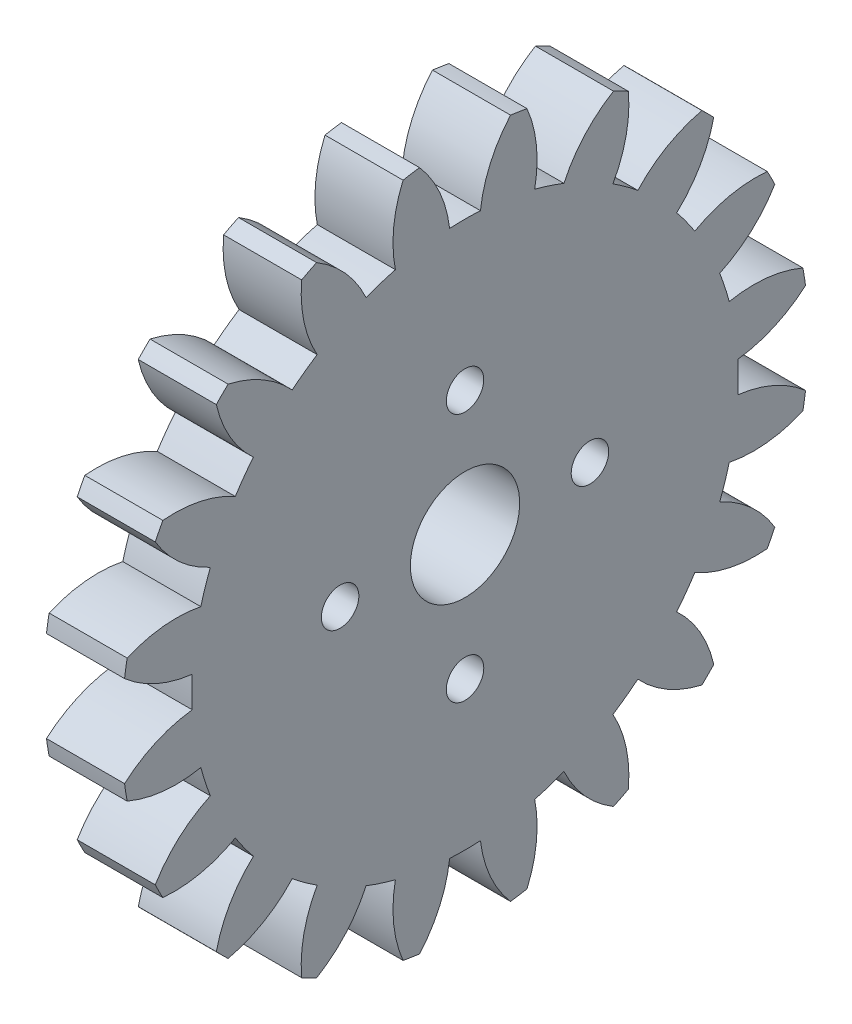
SolidWorks part; units mm, degrees
ref_plane "Plane1" through (0, 0, 0) normal (0, 0, 1) x (1, 0, 0)
ref_plane "Plane2" through (0, 0, 0) normal (0, 1, 0) x (1, 0, 0)
ref_plane "Plane3" through (0, 0, 0) normal (1, 0, 0) x (0, 0, -1)
sketch "HoldingSke" plane through (0, 0, 0) normal (0, 1, 0) x (1, 0, 0)
  line L0 (0, 0) -> (0.4698, -0.171)
  line L1 (-15, 0) -> (100, 0) construction
  line L2 (0, 0) -> (-2.1039, 2.3779)
  line L3 (0, 0) -> (-11.863, 4.5341)
  line L4 (0, 0) -> (8.1152, 2.9537)
  line L5 (0, 0) -> (-46.8476, -17.4728)
  line L6 (0, 0) -> (-4.1448, -2.7965)
  line L7 (-2.1039, 2.3779) -> (8.6586, 51.2059)
  line L8 (-76.2, 54.61) -> (-75.2, 54.61)
  line L9 (-71.009, 38.7566) -> (-53.1078, 45.2721)
  line L10 (-76.2, 71.12) -> (104.1128, 71.12)
  line L11 (0, 0) -> (-5, 0)
  line L12 (-76.2, 101.6) -> (-76.133, 101.6)
  line L13 (24.9733, 27.94) -> (52.9518, 28.4284)
  line L14 (24.9733, 27.94) -> (24.9743, 27.94)
  line L15 (24.9733, 27.94) -> (100.4006, 29.5858)
  line L16 (-63.627, -2) -> (-12.827, -2)
  circle A0 centre (0, 0) radius 3.5
  circle A1 centre (0, 0) radius 17.499
  circle A2 centre (0, 0) radius 37.5
  circle A3 centre (0, 0) radius 3.5
  dimension "MHD" = 34.998
  dimension "Hub_dia" = 75
  dimension "Bore" = 7
  dimension "MBD" = 7
  dimension "Num_teeth" = 20
  dimension "Pitch" = 0.5
  dimension "Overall_len" = 50
  dimension "Show_teeth" = 20
  dimension "Thickness" = 5
  dimension "OAL" = 50.0001
  dimension "T_dim" = 1
  dimension "Ap" = 20
  dimension "H" = 19.05
  dimension "Pitch_radius" = 180.3128
  dimension "Width" = 5
  dimension "Backlash" = 0.067
  dimension "Addendum_fac" = 1
  dimension "Dedendum_fac" = 1.25
  dimension "Clearance_fac" = 0.25
  dimension "Dedendum_add" = 0.001
  dimension "Module" = 2
sketch "BasProSke" plane through (0, 0, 0) normal (0, 1, 0) x (1, 0, 0)
  line L0 (-10, 0) -> (60, 0) construction
  line L1 (0, 0) -> (0, 22)
  line L2 (0, 0) -> (5, 0)
  line L3 (5, 0) -> (5, 22)
  line L4 (5, 22) -> (0, 22)
  dimension "Thickness" = 5
  dimension "Diameter" = 44
revolve "Base-Revolve" add sketch "BasProSke" angle 360 about L0
sketch "TooCutSke" plane through (0, 0, 0) normal (1, 0, 0) x (0, 0, -1)
  line L1 (0, 0) -> (0, 107) construction
  line L2 (0, 0) -> (-1.6864, 19.9288) construction
  line L3 (0, 0) -> (-6.2409, 39.4033) construction
  line L4 (-1.6864, 19.9288) -> (-3.1204, 19.7016) construction
  arc A0 (0.9862, 17.4712) -> (-0.9862, 17.4712) centre (0, 0) ccw
  arc A1 (2.9329, 21.8293) -> (-2.9329, 21.8293) centre (0, 0) ccw
  circle A2 centre (0, 0) radius 20 construction
  circle A3 centre (0, 0) radius 18.7939 construction
  arc A4 (-0.9862, 17.4712) -> (-2.9329, 21.8293) centre (-8.9313, 16.536) ccw
  arc A5 (2.9329, 21.8293) -> (0.9862, 17.4712) centre (8.9313, 16.536) ccw
  dimension "Root_dia" = 34.998
  dimension "Overcut_dia" = 44.0508
  dimension "Pitch_dia" = 40
  dimension "Base_dia" = 37.5877
  dimension "Flank_rad" = 8
  dimension "Half_ang" = 9
  dimension "Half_CT" = 1.4519
extrude "ToothCut" cut sketch "TooCutSke" along normal through all
fillet "Breaks" [suppressed] radius 0.04
fillet "RootFillets" [suppressed] radius 0.501
pattern_circular "TeethCuts" count 20 every 18 about axis through (-10, 0, 0) along (1, 0, 0) of "ToothCut", "RootFillets", "Breaks"
sketch "HubNeaOneSke" plane through (0, 0, 0) normal (-1, 0, 0) x (0, 0, 1)
  circle A0 centre (0, 0) radius 17.499
  dimension "Diameter" = 34.998
extrude "HubNearOne" [suppressed] add sketch "HubNeaOneSke" along normal blind 45.0001
sketch "HubNeaBotSke" plane through (0, 0, 0) normal (-1, 0, 0) x (0, 0, 1)
  circle A0 centre (0, 0) radius 17.499
  dimension "Diameter" = 34.998
extrude "HubNearBoth" [suppressed] add sketch "HubNeaBotSke" along normal blind 22.5
ref_plane "FarPln" through (5, 0, 0) normal (1, 0, 0) x (0, 0, -1)
sketch "HubFarSke" plane through (5, 0, 0) normal (1, 0, 0) x (0, 0, -1)
  circle A0 centre (0, 0) radius 17.499
  dimension "Diameter" = 34.998
extrude "HubFar" [suppressed] add sketch "HubFarSke" along normal blind 22.5
sketch "BorSke" plane through (0, 0, 0) normal (1, 0, 0) x (0, 0, -1)
  circle A0 centre (0, 0) radius 3.5
  dimension "Diameter" = 7
extrude "Bore" cut sketch "BorSke" along normal mid plane 100.0001
sketch "KeySke" plane through (0, 0, 0) normal (1, 0, 0) x (0, 0, -1)
  line L0 (-1, 0) -> (-1, 4.5)
  line L1 (-1, 4.5) -> (1, 4.5)
  line L2 (1, 4.5) -> (1, 0)
  line L3 (0, 0) -> (0, 34) construction
  line L4 (-1, 0) -> (1, 0)
  dimension "Offset" = 4.5
  dimension "Width" = 2
extrude "Keyway" [suppressed] cut sketch "KeySke" along normal mid plane 100.0001
pattern_circular "Keyway2" [suppressed] count 2 every 90 about axis through (-10, 0, 0) along (1, 0, 0)
sketch "Esquisse1" plane through (0, 0, 0) normal (-1, 0, 0) x (0, 0, 1)
  circle A0 centre (0, 0) radius 8 construction
  circle A1 centre (0, 8) radius 0.5
  point P5 (0, 0)
  dimension "D1" = 16
  dimension "D2" = 1
hole_wizard "Fraisage pour vis à tête fraisée M21" positions "Esquisse2" profile "Esquisse3" countersink size "M2" standard "ISO" end condition up to next
sketch "Esquisse2" plane through (0, 0, 0) normal (-1, 0, 0) x (0, 0, 1)
  point P0 (0, 8)
sketch "Esquisse3" plane through (0, 8, 0) normal (0, 1, 0) x (0, 0, 1)
  line L0 (0, 0) -> (0, 5)
  line L1 (0, 5) -> (1.2, 5)
  line L2 (1.2, 5) -> (1.2, 1)
  line L3 (1.2, 1) -> (2.2, 0)
  line L5 (2.2, 0) -> (0, 0)
  line L6 (-1.2, 1) -> (-2.2, 0) construction
  line L11 (0, -6.35) -> (0, 107.95) construction
  dimension "Diamètre du perçage jusqu'au prochain" = 2.4
  dimension "Profondeur du perçage jusqu'au prochain" = 5
  dimension "Diamètre du fraisage entrant" = 4.4
  dimension "Angle du fraisage entrant" = 90
pattern_circular "Répétition circulaire1" count 4 over 360 about axis through (0, 0, 0) along (1, 0, 0) of "Fraisage pour vis à tête fraisée M21"
equation "' \"Module@HoldingSke\" = 6.35"
equation "' \"Num_teeth@HoldingSke\" = 12"
equation "' \"Ap@HoldingSke\" =  20"
equation "' \"Ap@HoldingSke\" = 20"
equation "' \"Width@HoldingSke\" = 0.5 * 25.4"
equation "' \"Hub_dia@HoldingSke\"= 1 * 25.4"
equation "' \"Hub_dia@HoldingSke\" = 1 * 25.4"
equation "' \"Overall_len@HoldingSke\" = 1.0 * 25.4"
equation "' \"Bore@HoldingSke\" = 0.75 * 25.4"
equation "' \"T_dim@HoldingSke\" = 0.1 * 25.4"
equation "' \"Width@KeySke\" = 0.25 * 25.4"
equation "' \"Show_teeth@HoldingSke\" = 13"
equation "' \"Backlash@HoldingSke\" = 0.009 * 25.4"
equation "' \"Addendum_fac@HoldingSke\" = 1.0"
equation "' \"Dedendum_fac@HoldingSke\" = 1.25"
equation "' \"Dedendum_add@HoldingSke\" = 0.00005 * 25.4"
equation "' \"Clearance_fac@HoldingSke\" = 0.25"
equation "\"Pitch@HoldingSke\" = 1 / \"Module@HoldingSke\""
equation "\"Overcut_dia@TooCutSke\" = (\"Num_teeth@HoldingSke\" + 2 * \"Addendum_fac@HoldingSke\") / \"Pitch@HoldingSke\" + 0.002 * 25.4"
equation "\"Pitch_dia@TooCutSke\" = \"Num_teeth@HoldingSke\" / \"Pitch@HoldingSke\""
equation "\"Base_dia@TooCutSke\" = \"Num_teeth@HoldingSke\" / \"Pitch@HoldingSke\" * cos((\"Ap@HoldingSke\"  * 3.14159265 / 180))"
equation "\"Root_dia@TooCutSke\" = (\"Num_teeth@HoldingSke\" + 2) / \"Pitch@HoldingSke\" - 2 * (\"Addendum_fac@HoldingSke\" + \"Dedendum_fac@HoldingSke\") / \"Pitch@HoldingSke\" - \"Dedendum_add@HoldingSke\" * 2"
equation "\"Half_ang@TooCutSke\" = 180 / \"Num_teeth@HoldingSke\""
equation "\"Half_CT@TooCutSke\" = \"Num_teeth@HoldingSke\" / \"Pitch@HoldingSke\" * sin((3.14159265 / 2 / \"Num_teeth@HoldingSke\")) / 2 - 7 * \"Backlash@HoldingSke\" / 4"
equation "\"Flank_rad@TooCutSke\" = \"Num_teeth@HoldingSke\" / \"Pitch@HoldingSke\" / 5"
equation "\"Radius@RootFillets\" = \"Clearance_fac@HoldingSke\" / \"Pitch@HoldingSke\" + \"Dedendum_add@HoldingSke\""
equation "\"Break_rad@Breaks\" = 0.02 / \"Pitch@HoldingSke\""
equation "\"Thickness@HoldingSke\" = \"Width@HoldingSke\""
equation "\"OAL@HoldingSke\" = \"Thickness@HoldingSke\""
equation "\"MHD@HoldingSke\" = (\"Num_teeth@HoldingSke\" + 2) / \"Pitch@HoldingSke\" - 2 * (\"Addendum_fac@HoldingSke\" + \"Dedendum_fac@HoldingSke\")  / \"Pitch@HoldingSke\" - \"Dedendum_add@HoldingSke\" * 2"
equation "\"MBD@HoldingSke\" = (\"Num_teeth@HoldingSke\" + 2) / \"Pitch@HoldingSke\" - 2 * (\"Addendum_fac@HoldingSke\" + \"Dedendum_fac@HoldingSke\")  / \"Pitch@HoldingSke\" - \"Dedendum_add@HoldingSke\" * 2 - 0.002 * 25.4"
equation "\"MHD@HoldingSke\" = ((sgn( \"MHD@HoldingSke\" - \"Hub_dia@HoldingSke\" )-1)*( \"MHD@HoldingSke\" - \"Hub_dia@HoldingSke\" ))/-2+ \"Hub_dia@HoldingSke\""
equation "\"MBD@HoldingSke\" = ((sgn( \"MBD@HoldingSke\" - \"Bore@HoldingSke\" )-1)*( \"MBD@HoldingSke\" - \"Bore@HoldingSke\" ))/-2+ \"Bore@HoldingSke\""
equation "\"OAL@HoldingSke\" = ((sgn( \"OAL@HoldingSke\" - \"Overall_len@HoldingSke\" )+1)*( \"OAL@HoldingSke\" - \"Overall_len@HoldingSke\" ))/2 + \"Overall_len@HoldingSke\" + 0.000002 * 25.4"
equation "\"Num_teeth@TeethCuts\" = int( \"Show_teeth@HoldingSke\" ) + 1"
equation "\"Num_teeth@TeethCuts\" = ((sgn( \"Num_teeth@TeethCuts\" - \"Num_teeth@HoldingSke\" )-1)*( \"Num_teeth@TeethCuts\" - \"Num_teeth@HoldingSke\" ))/-2+ \"Num_teeth@HoldingSke\""
equation "\"Num_teeth@TeethCuts\" = ((sgn( \"Num_teeth@TeethCuts\" - 2.0)+1)*( \"Num_teeth@TeethCuts\" - 2.0))/2 +2.0"
equation "\"Angle@TeethCuts\" = 360.0 / \"Num_teeth@HoldingSke\""
equation "\"Diameter@BasProSke\" = (\"Num_teeth@HoldingSke\" + 2 * \"Addendum_fac@HoldingSke\") / \"Pitch@HoldingSke\""
equation "\"Thickness@BasProSke\"  = \"Thickness@HoldingSke\""
equation "' \"Fillet_rad@BasProSke\" =  \"Thickness@HoldingSke\" * 0.05"
equation "' \"Fillet_rad@BasProSke\" = \"Thickness@HoldingSke\" * 0.05"
equation "\"MHD@HoldingSke\" = ((sgn( \"MHD@HoldingSke\" - \"Root_dia@TooCutSke\" )-1)*( \"MHD@HoldingSke\" - \"Root_dia@TooCutSke\" ))/-2+ \"Root_dia@TooCutSke\""
equation "\"Diameter@HubNeaOneSke\" = \"MHD@HoldingSke\""
equation "\"Length@HubNearOne\" = \"OAL@HoldingSke\" - \"Thickness@BasProSke\""
equation "\"Diameter@HubNeaBotSke\" = \"MHD@HoldingSke\""
equation "\"Length@HubNearBoth\" = ( \"OAL@HoldingSke\" - \"Thickness@BasProSke\" ) / 2.0"
equation "\"Thickness@FarPln\" = \"Thickness@BasProSke\""
equation "\"Diameter@HubFarSke\" = \"MHD@HoldingSke\""
equation "\"Length@HubFar\" = ( \"OAL@HoldingSke\" - \"Thickness@BasProSke\" ) / 2.0"
equation "\"Diameter@BorSke\" = \"MBD@HoldingSke\""
equation "\"D1@Bore\" = \"OAL@HoldingSke\" * 2.0"
equation "\"D1@Keyway\" = \"OAL@HoldingSke\" * 2.0"
equation "\"Offset@KeySke\" = \"T_dim@HoldingSke\" + \"MBD@HoldingSke\" / 2.0"
